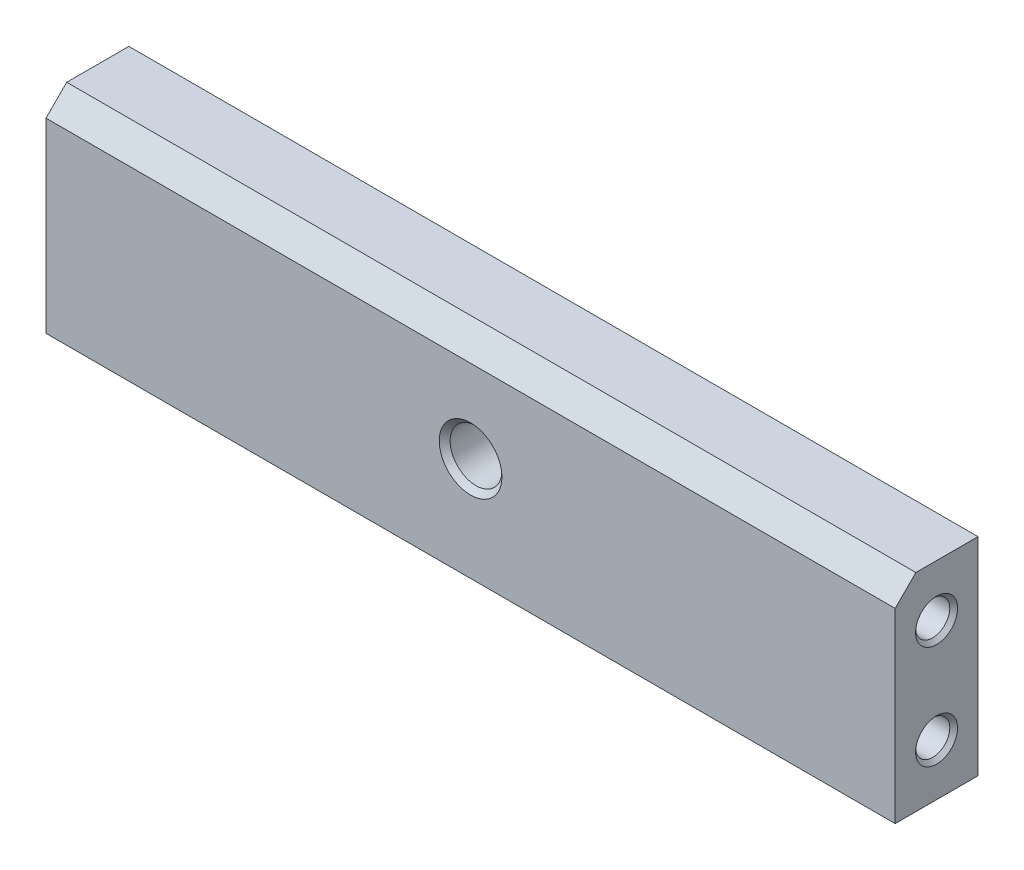
SolidWorks part; units mm, degrees
material "5052-O"
ref_plane "정면" through (0, 0, 0) normal (0, 0, 1) x (1, 0, 0)
ref_plane "윗면" through (0, 0, 0) normal (0, 1, 0) x (1, 0, 0)
ref_plane "우측면" through (0, 0, 0) normal (1, 0, 0) x (0, 0, -1)
sketch "스케치1" plane through (0, 0, 0) normal (0, 0, 1) x (1, 0, 0)
  line L1 (0, 0) -> (82, 0)
  line L2 (0, 0) -> (0, 20)
  line L3 (0, 20) -> (82, 20)
  line L4 (82, 0) -> (82, 20)
  dimension "D1" = 82
  dimension "D2" = 20
extrude "보스-돌출1" add sketch "스케치1" along normal blind 8
ref_plane "평면1" through (41, 0, 0) normal (-1, 0, 0) x (0, 0, 1)
hole_wizard "M6 나사 구멍1" positions "스케치2" profile "스케치3" tap size "M6" standard "ISO" end condition up to next
sketch "스케치2" plane through (0, 0, 8) normal (0, 0, 1) x (1, 0, 0)
  line L0 (82, 20) -> (0, 20) construction
  line L1 (0, 20) -> (0, 0) construction
  point P0 (41, 10)
  point P6 (41, 20)
  point P10 (0, 10)
sketch "스케치3" plane through (41, 10, 8) normal (1, 0, 0) x (0, -1, 0)
  line L0 (0, 0) -> (0, 8)
  line L1 (0, 8) -> (2.5, 8)
  line L2 (2.5, 8) -> (2.5, 0.525)
  line L3 (2.5, 0.525) -> (3.025, 0)
  line L5 (3.025, 0) -> (0, 0)
  line L6 (-2.5, 0.525) -> (-3.025, 0) construction
  line L11 (0, -6.35) -> (0, 107.95) construction
  dimension "관통 탭 드릴 지름" = 5
  dimension "관통 탭 드릴 깊이" = 8
  dimension "표면 카운터싱크 지름" = 6.05
  dimension "표면 카운터싱크 각도" = 90
cosmetic thread "구멍 나사산1" parameters "D2"=6
hole_wizard "M4 나사 구멍1" positions "스케치4" profile "스케치5" tap size "M4" standard "ISO"
sketch "스케치4" plane through (0, 0, 0) normal (-1, 0, 0) x (0, 0, 1)
  line L0 (4, 15) -> (4, 5)
  line L2 (8, 20) -> (0, 20) construction
  line L3 (0, 20) -> (0, 0) construction
  point P0 (4, 15)
  point P2 (4, 5)
  point P11 (4, 20)
  point P12 (4, 10)
  point P15 (0, 10)
  dimension "D1" = 10
sketch "스케치5" plane through (0, 15, 4) normal (0, 1, 0) x (0, 0, 1)
  line L0 (0, 0) -> (0, 12.4914)
  line L1 (0, 12.4914) -> (1.65, 11.5)
  line L2 (1.65, 11.5) -> (1.65, 0.375)
  line L3 (1.65, 0.375) -> (2.025, 0)
  line L5 (2.025, 0) -> (0, 0)
  line L6 (-1.65, 0.375) -> (-2.025, 0) construction
  line L10 (0, 12.4914) -> (-1.65, 11.5) construction
  line L11 (0, -6.35) -> (0, 107.95) construction
  dimension "탭 드릴 지름" = 3.3
  dimension "탭 드릴 깊이" = 11.5
  dimension "표면 카운터싱크 지름" = 4.05
  dimension "표면 카운터싱크 각도" = 90
  dimension "드릴 각도" = 118
cosmetic thread "구멍 나사산2" parameters "D1"=8, "D2"=4
cosmetic thread "구멍 나사산3" parameters "D1"=8, "D2"=4
mirror "대칭 복사1" about plane through (41, 0, 0) normal (-1, 0, 0) of "M4 나사 구멍1"
cosmetic thread "구멍 나사산4" parameters "D1"=8, "D2"=4
cosmetic thread "구멍 나사산5" parameters "D1"=8, "D2"=4
chamfer "모따기1" distance 2 angle 45 1 edges at (41, 20, 8)
